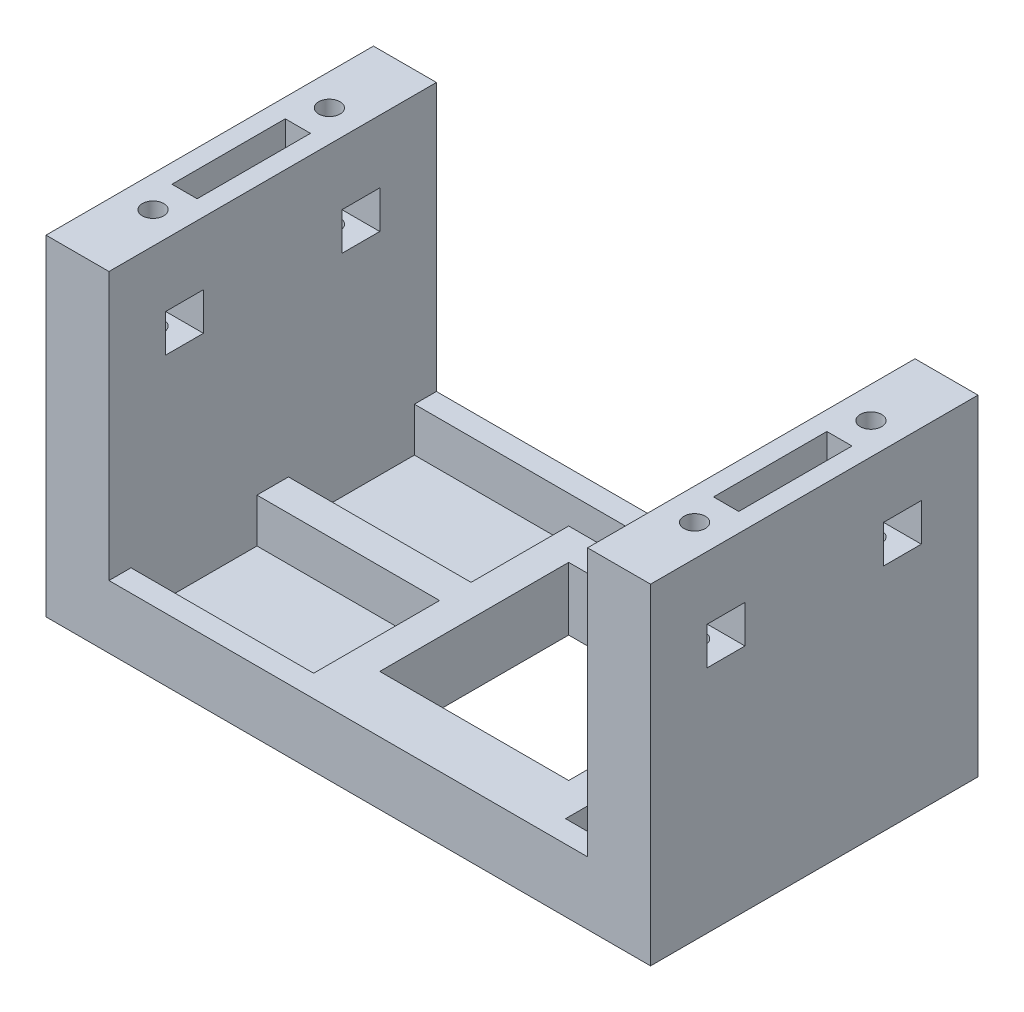
SolidWorks part; units mm, degrees
material "ABS"
ref_plane "Front Plane" through (0, 0, 0) normal (0, 0, 1) x (1, 0, 0)
ref_plane "Top Plane" through (0, 0, 0) normal (0, 1, 0) x (1, 0, 0)
ref_plane "Right Plane" through (0, 0, 0) normal (1, 0, 0) x (0, 0, -1)
other "Center of Mass"
sketch "Sketch1" plane through (0, 0, 0) normal (0, 1, 0) x (1, 0, 0)
  line L0 (0, -55) -> (0, 55) construction
  line L1 (-61, 26) -> (35, 26)
  line L2 (-61, 26) -> (-61, -26)
  line L3 (-61, -26) -> (35, -26)
  line L4 (35, 26) -> (35, -26)
  line L5 (-55, 0) -> (55, 0) construction
  dimension "D1" = 96
  dimension "D2" = 52
  dimension "D3" = 35
  dimension "D4" = 26
extrude "Boss-Extrude1" add sketch "Sketch1" along normal blind 10
sketch "Sketch3" plane through (0, 10, 0) normal (0, 1, 0) x (1, 0, 0)
  line L0 (35, -26) -> (35, 26) construction
  line L1 (-17, 13) -> (13, 13)
  line L2 (-17, 13) -> (-17, -17)
  line L3 (-17, -17) -> (13, -17)
  line L4 (13, 13) -> (13, -17)
  line L7 (35, 26) -> (-61, 26) construction
  dimension "D1" = 22
  dimension "D2" = 30
  dimension "D3" = 13
  dimension "D4" = 30
extrude "Cut-Extrude1" cut sketch "Sketch3" against normal blind 10
sketch "Sketch4" plane through (0, 10, 0) normal (0, 1, 0) x (1, 0, 0)
  line L0 (-61, -26) -> (35, -26) construction
  line L1 (35, 26) -> (25, 26)
  line L2 (35, 26) -> (35, -26)
  line L3 (35, -26) -> (25, -26)
  line L4 (25, 26) -> (25, -26)
  line L7 (-61, 26) -> (-51, 26)
  line L8 (-61, 26) -> (-61, -26)
  line L9 (-61, -26) -> (-51, -26)
  line L10 (-51, 26) -> (-51, -26)
  dimension "D1" = 10
  dimension "D2" = 10
extrude "Boss-Extrude2" add sketch "Sketch4" along normal blind 42.5
sketch "Sketch5" plane through (0, 10, 0) normal (0, 1, 0) x (1, 0, 0)
  line L0 (-51, -26) -> (25, -26) construction
  line L1 (-51, 22.5) -> (25, 22.5)
  line L2 (-51, 22.5) -> (-51, 2.5)
  line L3 (-51, -22.5) -> (-22, -22.5)
  line L4 (25, 22.5) -> (25, 2.5)
  line L5 (-22, 18) -> (18, 18)
  line L6 (-22, 18) -> (-22, 2.5)
  line L8 (18, 18) -> (18, 2.5)
  line L9 (25, 26) -> (25, -26) construction
  line L10 (-61, 26) -> (-61, -26) construction
  line L11 (-2, -17) -> (-2, 30.9744) construction
  line L12 (18, 2.5) -> (25, 2.5)
  line L13 (25, -2.5) -> (25, -22.5)
  line L14 (18, -2.5) -> (25, -2.5)
  line L16 (-4.5, 22.5) -> (0.5, 22.5)
  line L17 (-4.5, 22.5) -> (-4.5, 18)
  line L18 (-4.5, 18) -> (0.5, 18)
  line L19 (0.5, 22.5) -> (0.5, 18)
  line L20 (-22, 2.5) -> (-51, 2.5)
  line L21 (18, -2.5) -> (18, -20)
  line L22 (-22, -2.5) -> (-51, -2.5)
  line L23 (18, -22.5) -> (25, -22.5)
  line L24 (-17, -17) -> (13, -17) construction
  line L27 (13, 13) -> (-17, 13) construction
  line L28 (-17, 13) -> (-17, -17) construction
  line L29 (13, -17) -> (13, 13) construction
  line L31 (-30.4177, 0) -> (30.4177, 0) construction
  line L32 (-51, -2.5) -> (-51, -22.5)
  line L33 (-22, -2.5) -> (-22, -20)
  line L35 (-22, -20) -> (-22, -22.5)
  line L36 (18, -20) -> (18, -22.5)
  dimension "D1" = 10
  dimension "D2" = 45
  dimension "D3" = 3.5
  dimension "D4" = 0
  dimension "D5" = 2.5
  dimension "D6" = 2.5
  dimension "D7" = 5
  dimension "D8" = 5
  dimension "D9" = 5
  dimension "D11" = 2.5
  dimension "D12" = 2.5
  dimension "D13" = 2.5
  dimension "D14" = 2.5
extrude "Cut-Extrude2" cut sketch "Sketch5" against normal blind 25
sketch "Sketch10" plane through (35, 0, 0) normal (1, 0, 0) x (0, 0, -1)
  line L1 (26, 52.5) -> (26, 0) construction
  line L2 (11, 36.5) -> (17, 36.5)
  line L3 (11, 36.5) -> (11, 42.5)
  line L4 (11, 42.5) -> (17, 42.5)
  line L5 (17, 36.5) -> (17, 42.5)
  line L6 (11, 36.5) -> (17, 42.5) construction
  line L7 (11, 42.5) -> (17, 36.5) construction
  line L8 (-26, 52.5) -> (26, 52.5) construction
  line L9 (0, 79.5181) -> (0, 55.2752) construction
  line L10 (0, 28.875) -> (0, -28.875) construction
  line L11 (-11, 36.5) -> (-17, 36.5)
  line L12 (-17, 36.5) -> (-17, 42.5)
  line L13 (-11, 42.5) -> (-17, 42.5)
  line L14 (-11, 36.5) -> (-11, 42.5)
  point P0 (14, 39.5)
  dimension "D1" = 12
  dimension "D2" = 6
  dimension "D3" = 6
  dimension "D4" = 10
extrude "Cut-Extrude7" cut sketch "Sketch10" against normal through all
sketch "Sketch11" plane through (0, 52.5, 0) normal (0, 1, 0) x (1, 0, 0)
  line L0 (-61, 26) -> (35, 26) construction
  line L1 (-58, 9) -> (-54, 9)
  line L2 (-58, 9) -> (-58, -9)
  line L3 (-58, -9) -> (-54, -9)
  line L4 (-54, 9) -> (-54, -9)
  line L5 (-13, 26) -> (-13, -31.3769) construction
  line L6 (-61, 26) -> (-61, -26) construction
  line L7 (-51, -26) -> (-51, 26) construction
  line L9 (32, -9) -> (28, -9)
  line L10 (28, 9) -> (28, -9)
  line L11 (32, 9) -> (32, -9)
  line L12 (32, 9) -> (28, 9)
  line L13 (-28.875, 0) -> (28.875, 0) construction
  circle A0 centre (-56, 14) radius 1.7
  circle A1 centre (-56, -14) radius 1.7
  circle A2 centre (30, -14) radius 1.7
  circle A3 centre (30, 14) radius 1.7
  dimension "D3" = 3.4
  dimension "D10" = 3.4
  dimension "D1" = 5
  dimension "D2" = 14
  dimension "D4" = 18
  dimension "D5" = 3
  dimension "D6" = 3
  dimension "D7" = 9
  dimension "D8" = 5
  dimension "D9" = 14
extrude "Cut-Extrude8" cut sketch "Sketch11" against normal blind 60
sketch "Sketch14" plane through (0, 0, 0) normal (0, -1, 0) x (1, 0, 0)
  line L1 (-61, 26) -> (35, 26)
  line L2 (-61, 26) -> (-61, -26)
  line L3 (-61, -26) -> (35, -26)
  line L4 (35, 26) -> (35, -26)
  line L5 (-17, 17) -> (13, 17)
  line L6 (-17, 17) -> (-17, -13)
  line L7 (-17, -13) -> (13, -13)
  line L8 (13, 17) -> (13, -13)
extrude "Boss-Extrude3" add sketch "Sketch14" against normal blind 3
